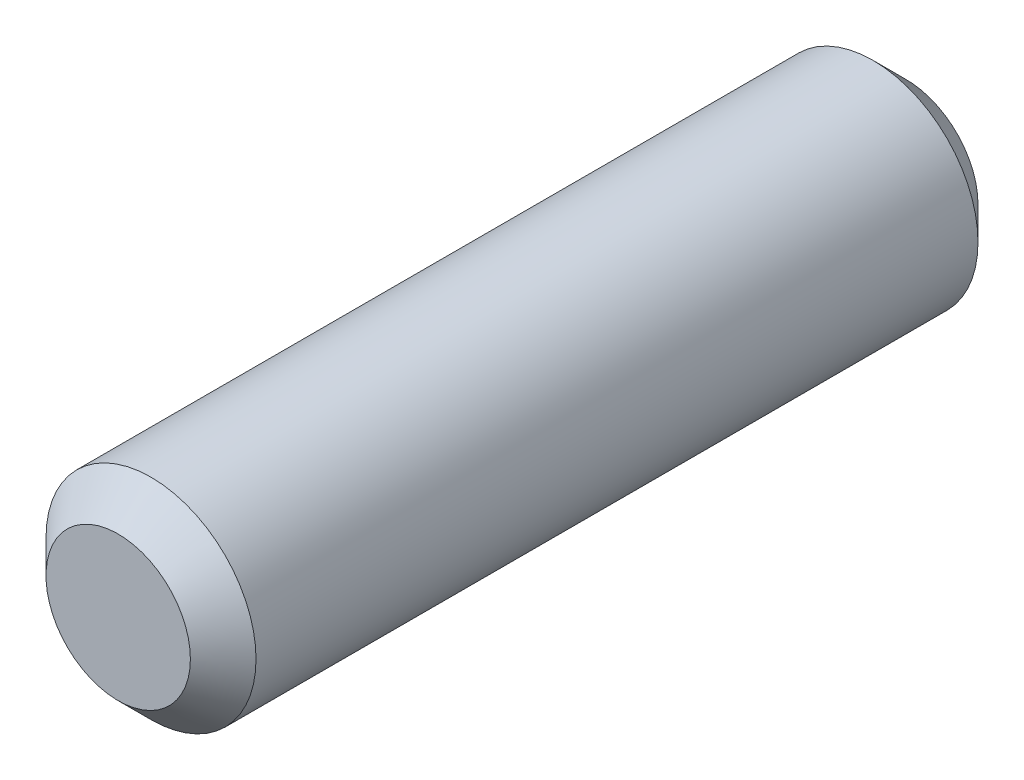
SolidWorks part; units mm, degrees
ref_plane "Płaszczyzna przednia" through (0, 0, 0) normal (0, 0, 1) x (1, 0, 0)
ref_plane "Płaszczyzna górna" through (0, 0, 0) normal (0, 1, 0) x (1, 0, 0)
ref_plane "Płaszczyzna prawa" through (0, 0, 0) normal (1, 0, 0) x (0, 0, -1)
sketch "Szkic1" plane through (0, 0, 0) normal (0, 0, 1) x (1, 0, 0)
  circle A0 centre (0, 0) radius 0.8
  dimension "D1" = 1.6
extrude "Dodanie-wyciągnięcie1" add sketch "Szkic1" along normal blind 6
chamfer "Sfazowanie1" distance 0.25 angle 45 2 edges at (0.8, 0, 0) (0.8, 0, 6)
